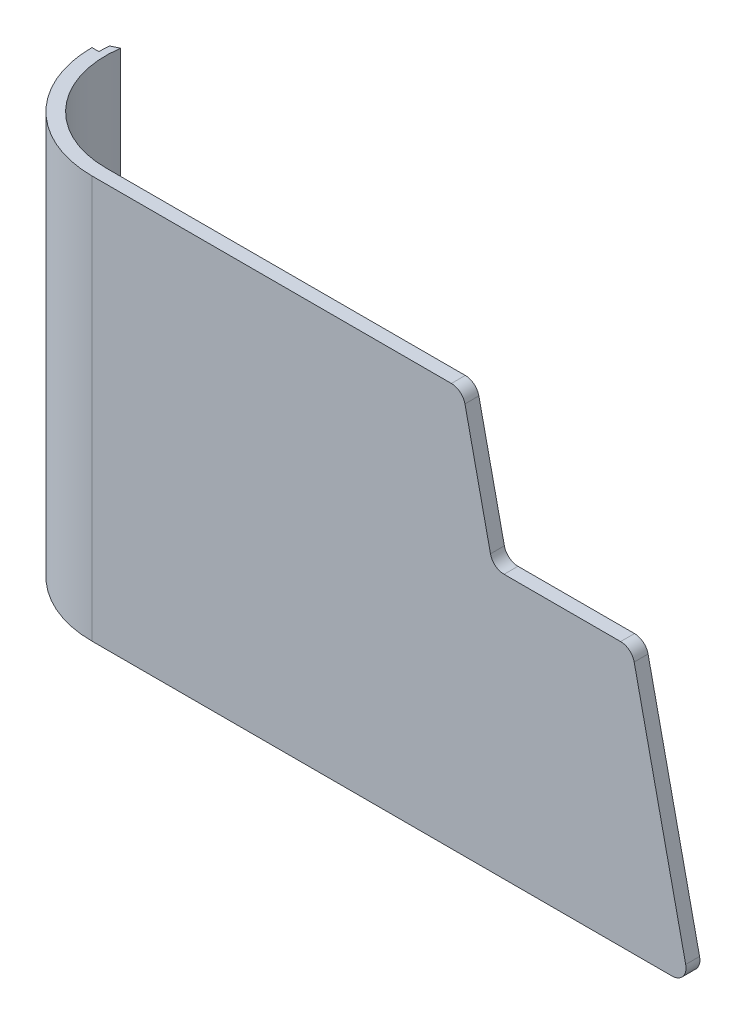
SolidWorks part; units mm, degrees
ref_plane "Front Plane" through (0, 0, 0) normal (0, 0, 1) x (1, 0, 0)
ref_plane "Top Plane" through (0, 0, 0) normal (0, 1, 0) x (1, 0, 0)
ref_plane "Right Plane" through (0, 0, 0) normal (1, 0, 0) x (0, 0, -1)
sketch "Sketch1" plane through (0, 0, 0) normal (0, 1, 0) x (1, 0, 0)
  line L0 (61.8667, 0) -> (-71.7128, 0) construction
  line L1 (-50, -14) -> (36, -14)
  line L4 (-50, -16) -> (36, -16)
  line L5 (36, 16) -> (36, 14.0896)
  line L8 (-50, -14) -> (34, -14) construction
  line L9 (-50, 14) -> (34, 14) construction
  line L10 (34, 14) -> (34, -14) construction
  line L11 (36, -14) -> (36, -16)
  line L12 (36, 16) -> (36, -16) construction
  line L13 (-64.9287, 1.4612) -> (-63.8564, 2)
  line L14 (-66, 0) -> (-65, 0)
  line L16 (-50, 16) -> (36, 16) construction
  arc A0 (-66, 0) -> (-50, -16) centre (-50, 0) ccw
  arc A1 (-63.8564, 2) -> (-50, -14) centre (-50, 0) ccw
  arc A2 (-64.9287, 1.4612) -> (-65, 0) centre (-50, 0) ccw
  arc A3 (-50, 16) -> (-50, -16) centre (-50, 0) ccw construction
  arc A4 (-50, 14) -> (-50, -14) centre (-50, 0) ccw construction
  dimension "D6" = 2
  dimension "D2" = 14
  dimension "D5" = 15
  dimension "D1" = 50
  dimension "D3" = 86
  dimension "D4" = 2
  dimension "D7" = 1.2
extrude "Boss-Extrude1" add sketch "Sketch1" along normal blind 58 contours A0 L4 L11 L1 A1 L13 A2 L14
sketch "Sketch2" plane through (0, 0, 16) normal (0, 0, 1) x (1, 0, 0)
  line L0 (36, 0) -> (27.7147, 38)
  line L1 (-50, 0) -> (36, 0) construction
  line L2 (27.7147, 38) -> (7.7147, 38)
  line L3 (7.7147, 38) -> (3.354, 58)
  line L4 (-50, 58) -> (36, 58) construction
  line L5 (36, 58) -> (36, 0) construction
  line L6 (3.354, 58) -> (36, 58)
  line L7 (36, 58) -> (36, 0)
  dimension "D1" = 38
  dimension "D2" = 102.3
  dimension "D3" = 20
extrude "Cut-Extrude1" cut sketch "Sketch2" against normal through all
fillet "Fillet1" radius 2 4 edges at (7.7147, 38, 15) (3.354, 58, 15) (27.7147, 38, 15) (36, 0, 15)
